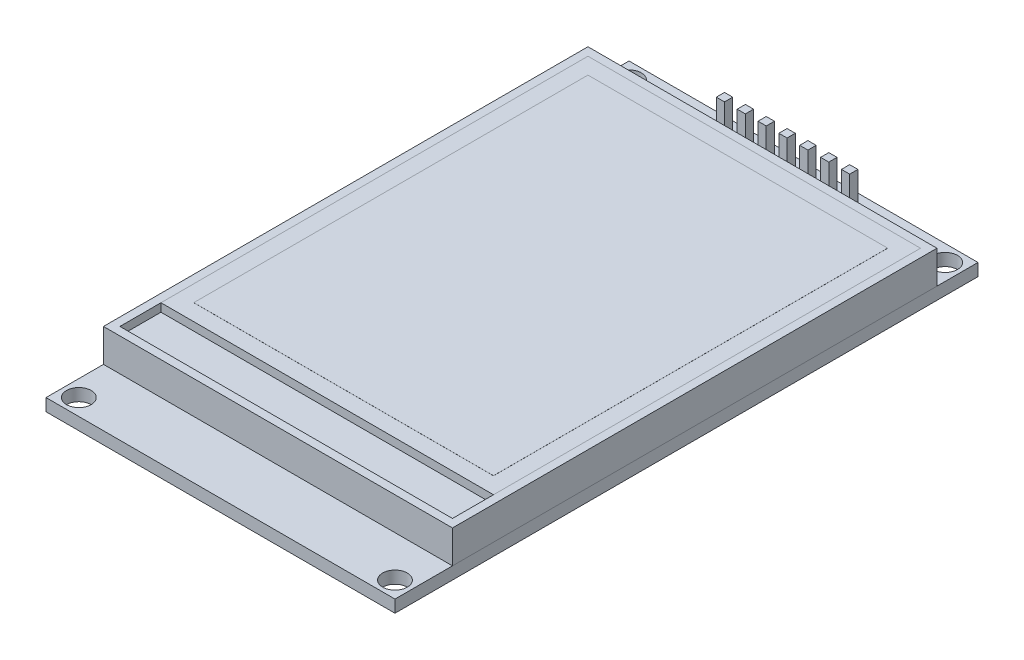
SolidWorks part; units mm, degrees
material "ABS"
ref_plane "Front Plane" through (0, 0, 0) normal (0, 0, 1) x (1, 0, 0)
ref_plane "Top Plane" through (0, 0, 0) normal (0, 1, 0) x (1, 0, 0)
ref_plane "Right Plane" through (0, 0, 0) normal (1, 0, 0) x (0, 0, -1)
sketch "Sketch1" plane through (0, 0, 0) normal (0, 1, 0) x (1, 0, 0)
  line L1 (-21.25, 35.5) -> (21.25, 35.5)
  line L2 (-21.25, 35.5) -> (-21.25, -35.5)
  line L3 (-21.25, -35.5) -> (21.25, -35.5)
  line L4 (21.25, 35.5) -> (21.25, -35.5)
  line L5 (0, -35.5) -> (0, 35.5) construction
  line L6 (-21.25, 0) -> (21.25, 0) construction
  point P0 (0, 0)
  dimension "D1" = 42.5
  dimension "D2" = 71
extrude "Boss-Extrude1" add sketch "Sketch1" along normal blind 1.5
sketch "Sketch7" plane through (0, 1.5, 0) normal (0, 1, 0) x (1, 0, 0)
  line L0 (-21.25, 35.5) -> (21.25, 35.5) construction
  line L1 (-21.25, 35.5) -> (-21.25, -35.5) construction
  circle A0 centre (-19.25, 33.5) radius 1.5
  dimension "D1" = 3
  dimension "D2" = 2
  dimension "D3" = 2
extrude "Cut-Extrude2" cut sketch "Sketch7" against normal through all
mirror "Mirror1" about plane through (0, 0, 0) normal (0, 0, 1) of "Cut-Extrude2" second plane through (0, 0, 0) second plane normal (1, 0, 0)
sketch "Sketch8" plane through (0, 1.5, 0) normal (0, 1, 0) x (1, 0, 0)
  line L0 (0, -10.821) -> (0, 10.821) construction
  line L1 (-0.5, 34) -> (0.5, 34)
  line L2 (-0.5, 34) -> (-0.5, 33)
  line L3 (-0.5, 33) -> (0.5, 33)
  line L4 (0.5, 34) -> (0.5, 33)
  line L5 (0, 33) -> (0, 34) construction
  line L6 (-0.5, 33.5) -> (0.5, 33.5) construction
  line L7 (-21.25, 35.5) -> (21.25, 35.5) construction
  point P0 (0, 33.5)
  dimension "D1" = 2
  dimension "D2" = 1
extrude "Boss-Extrude5" add sketch "Sketch8" along normal blind 4 and the other way blind 8
pattern_linear "LPattern1" count 4 spacing 2.54 along (1, 0, 0) count 4 spacing 2.54 along (-1, 0, 0) of "Boss-Extrude5"
sketch "Sketch2" plane through (0, 1.5, 0) normal (0, 1, 0) x (1, 0, 0)
  line L1 (-21.25, 30.5) -> (21.25, 30.5)
  line L2 (-21.25, 30.5) -> (-21.25, -28.5)
  line L3 (-21.25, -28.5) -> (21.25, -28.5)
  line L4 (21.25, 30.5) -> (21.25, -28.5)
  line L6 (-21.25, 35.5) -> (-21.25, -35.5) construction
  line L7 (21.25, 35.5) -> (21.25, -35.5) construction
  line L8 (-21.25, 35.5) -> (21.25, 35.5) construction
  line L9 (-21.25, -35.5) -> (21.25, -35.5) construction
  line L10 (-21.25, 1) -> (21.25, 1) construction
  point P4 (0, 1)
  dimension "D1" = 5
  dimension "D2" = 7
extrude "Boss-Extrude2" add sketch "Sketch2" along normal blind 4 separate body
sketch "Sketch3" plane through (0, 5.5, 0) normal (0, 1, 0) x (1, 0, 0)
  line L1 (-20.25, 29.5) -> (20.25, 29.5)
  line L2 (-20.25, 29.5) -> (-20.25, -27.5)
  line L3 (-20.25, -27.5) -> (20.25, -27.5)
  line L4 (20.25, 29.5) -> (20.25, -27.5)
  line L5 (0, -10.821) -> (0, 10.821) construction
  line L6 (-21.25, 30.5) -> (21.25, 30.5) construction
  line L7 (-21.25, 35.5) -> (-21.25, -35.5) construction
  line L9 (-21.25, 1) -> (21.25, 1) construction
  point P8 (0, 29.5)
  point P12 (-20.25, 1)
  dimension "D1" = 1
  dimension "D2" = 1
extrude "Cut-Extrude1" cut sketch "Sketch3" against normal through all
sketch "Sketch5" plane through (0, 1.5, 0) normal (0, 1, 0) x (1, 0, 0)
  line L4 (20.25, 29.5) -> (-20.25, 29.5)
  line L5 (20.25, -27.5) -> (20.25, 29.5)
  line L6 (-20.25, -27.5) -> (20.25, -27.5)
  line L7 (-20.25, 29.5) -> (-20.25, -27.5)
  line L8 (20.25, 29.5) -> (-20.25, 29.5)
  line L9 (20.25, -27.5) -> (20.25, 29.5)
  line L10 (-20.25, -27.5) -> (20.25, -27.5)
  line L11 (-20.25, 29.5) -> (-20.25, -27.5)
  dimension "D1" = 0
extrude "Boss-Extrude3" add sketch "Sketch5" along normal up to surface (4 mm away) separate body up to face at (0, 5.5, -1)
sketch "Sketch9" plane through (0, 5.5, 0) normal (0, 1, 0) x (1, 0, 0)
  line L0 (20.25, 29.5) -> (20.25, -27.5) construction
  line L1 (-20.25, -27.5) -> (20.25, -27.5)
  line L2 (-20.25, -27.5) -> (-20.25, -22.5)
  line L3 (-20.25, -22.5) -> (20.25, -22.5)
  line L4 (20.25, -27.5) -> (20.25, -22.5)
  dimension "D1" = 5
extrude "Cut-Extrude3" cut sketch "Sketch9" against normal blind 1
sketch "Sketch6" plane through (0, 5.5, 0) normal (0, 1, 0) x (1, 0, 0)
  line L0 (0, -10.821) -> (0, 10.821) construction
  line L1 (-18.25, 27.5) -> (18.25, 27.5)
  line L2 (-18.25, 27.5) -> (-18.25, -20.5)
  line L3 (-18.25, -20.5) -> (18.25, -20.5)
  line L4 (18.25, 27.5) -> (18.25, -20.5)
  line L5 (21.25, 35.5) -> (-21.25, 35.5) construction
  line L6 (-20.25, 29.5) -> (20.25, 29.5) construction
  line L7 (-20.25, 29.5) -> (-20.25, -27.5) construction
  line L12 (20.25, 29.5) -> (-20.25, 29.5) construction
  line L13 (-20.25, 29.5) -> (-20.25, -27.5) construction
  line L14 (-21.25, 35.5) -> (-21.25, -35.5) construction
  line L15 (-20.25, -22.5) -> (20.25, -22.5) construction
  line L16 (20.25, -22.5) -> (-20.25, -22.5) construction
  line L17 (-21.25, -35.5) -> (21.25, -35.5) construction
  point P4 (0, 27.5)
  dimension "D1" = 2
  dimension "D2" = 2
  dimension "D3" = 2
  dimension "D4" = 13
  dimension "D7" = 6
  dimension "D8" = 1
extrude "Boss-Extrude4" add sketch "Sketch6" along normal blind 0.01
